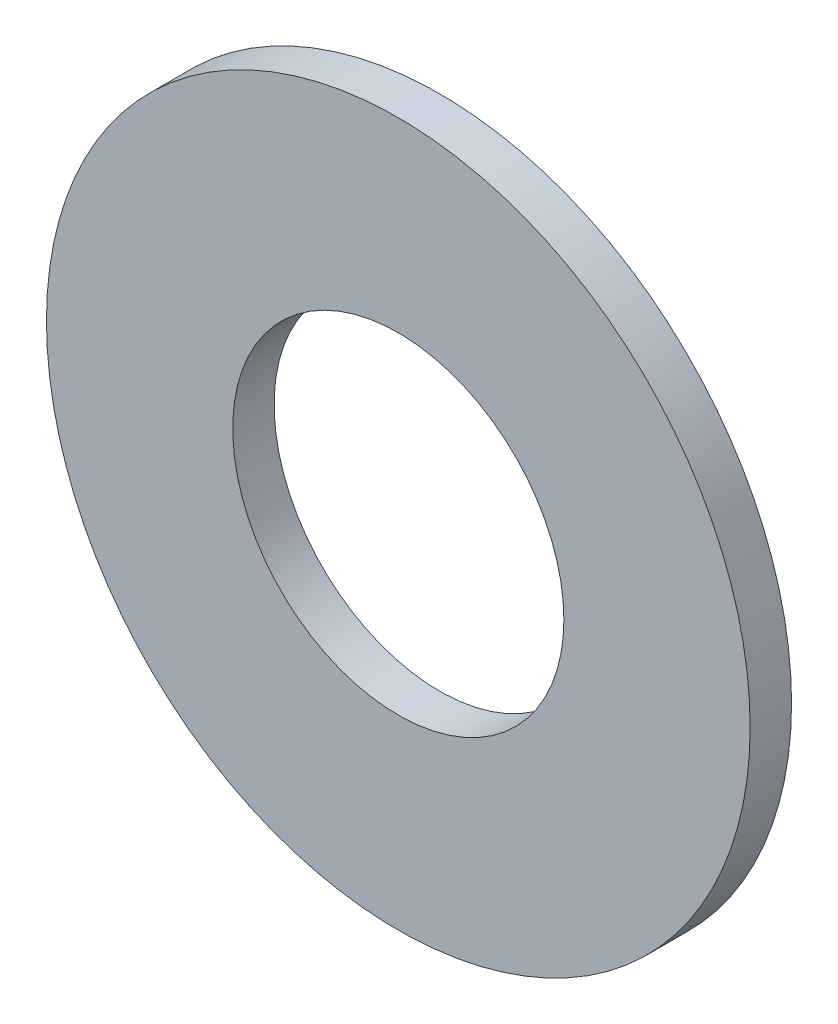
SolidWorks part; units mm, degrees
ref_plane "정면" through (0, 0, 0) normal (0, 0, 1) x (1, 0, 0)
ref_plane "윗면" through (0, 0, 0) normal (0, 1, 0) x (1, 0, 0)
ref_plane "우측면" through (0, 0, 0) normal (1, 0, 0) x (0, 0, -1)
sketch "스케치1" plane through (0, 0, 0) normal (0, 0, 1) x (1, 0, 0)
  circle A0 centre (0, 0) radius 8.5
  circle A1 centre (0, 0) radius 4
  dimension "D1" = 17
  dimension "D2" = 8
extrude "보스-돌출1" add sketch "스케치1" along normal blind 1
